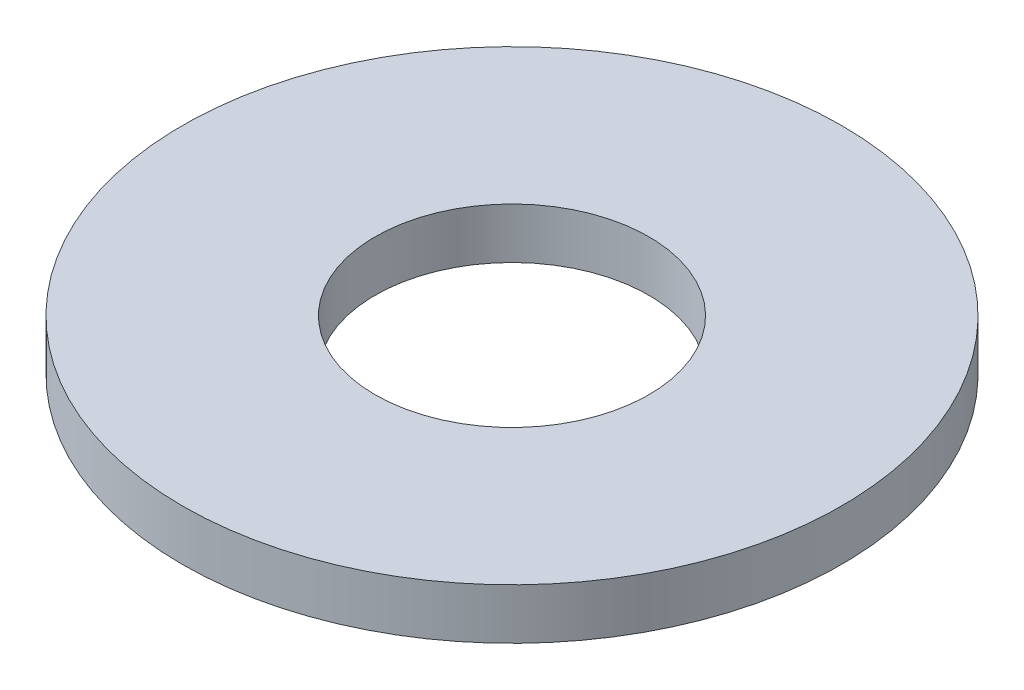
SolidWorks part; units mm, degrees
ref_plane "Plan de face" through (0, 0, 0) normal (0, 0, 1) x (1, 0, 0)
ref_plane "Plan de dessus" through (0, 0, 0) normal (0, 1, 0) x (1, 0, 0)
ref_plane "Plan de droite" through (0, 0, 0) normal (1, 0, 0) x (0, 0, -1)
sketch "Esquisse1" plane through (0, 0, 0) normal (0, 1, 0) x (1, 0, 0)
  circle A0 centre (0, 0) radius 1.35
  circle A1 centre (0, 0) radius 3.25
  dimension "D1" = 2.7
  dimension "D2" = 6.5
extrude "Boss.-Extru.1" add sketch "Esquisse1" along normal mid plane 0.5
